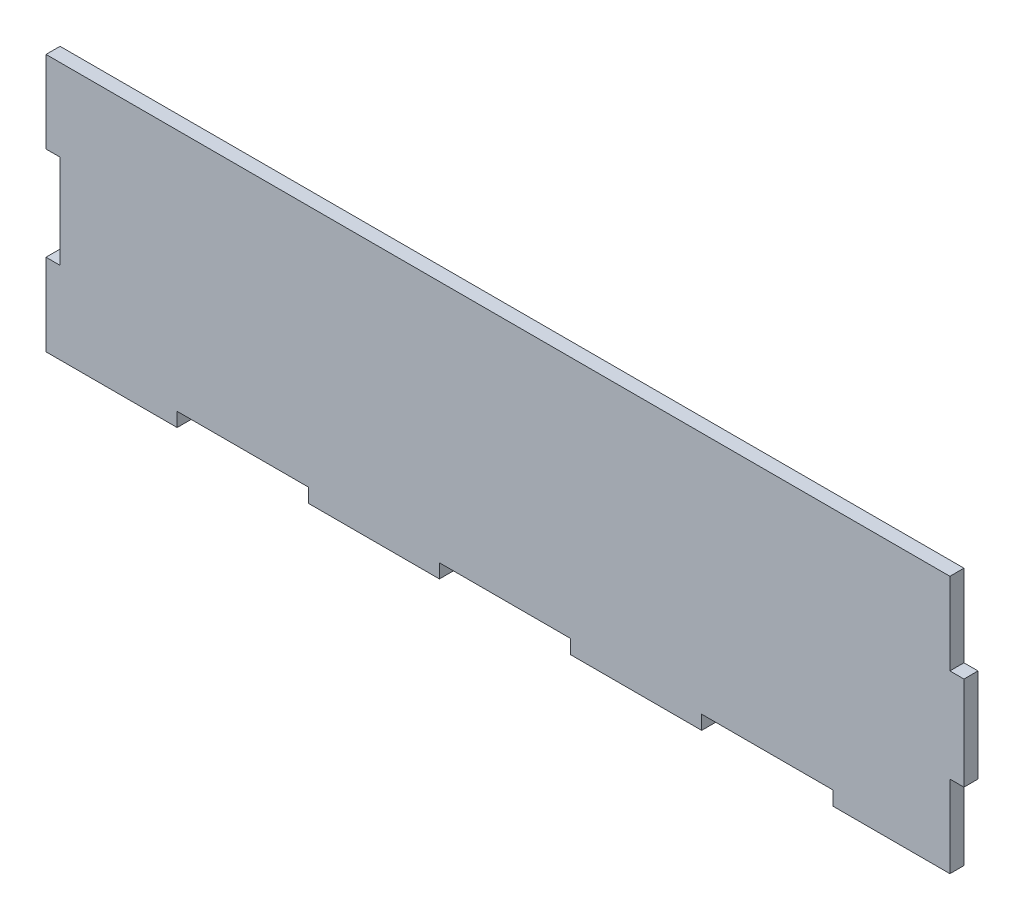
SolidWorks part; units mm, degrees
ref_plane "Front Plane" through (0, 0, 0) normal (0, 0, 1) x (1, 0, 0)
ref_plane "Top Plane" through (0, 0, 0) normal (0, 1, 0) x (1, 0, 0)
ref_plane "Right Plane" through (0, 0, 0) normal (1, 0, 0) x (0, 0, -1)
sketch "Sketch1" plane through (0, 0, 0) normal (0, 0, 1) x (1, 0, 0)
  line L0 (-98, -10) -> (-95, -10)
  line L1 (-98, -27.5) -> (98, -27.5)
  line L2 (-98, -27.5) -> (-98, 27.5)
  line L3 (-98, 27.5) -> (98, 27.5)
  line L4 (98, -27.5) -> (98, 27.5)
  line L5 (-98, -27.5) -> (98, 27.5) construction
  line L6 (-98, 27.5) -> (98, -27.5) construction
  line L7 (-95, -10) -> (-95, 10)
  line L8 (-95, 10) -> (-98, 10)
  line L9 (98, -10) -> (95, -10)
  line L10 (95, -10) -> (95, -27.5)
  line L11 (98, 10) -> (95, 10)
  line L12 (95, 10) -> (95, 27.5)
  line L14 (-70, -27.5) -> (-70, -24.5)
  line L15 (-70, -24.5) -> (-42, -24.5)
  line L16 (-42, -24.5) -> (-42, -27.5)
  line L18 (-14, -27.5) -> (-14, -24.5)
  line L19 (-14, -24.5) -> (14, -24.5)
  line L20 (14, -24.5) -> (14, -27.5)
  line L22 (42, -27.5) -> (42, -24.5)
  line L23 (42, -24.5) -> (70, -24.5)
  line L24 (70, -24.5) -> (70, -27.5)
  point P0 (0, 0)
  dimension "D1" = 196
  dimension "D2" = 55
  dimension "D3" = 20
  dimension "D4" = 17.5
  dimension "D5" = 3
  dimension "D6" = 3
  dimension "D7" = 3
  dimension "D8" = 28
  dimension "D9" = 28
  dimension "D10" = 28
  dimension "D11" = 28
  dimension "D12" = 28
  dimension "D13" = 28
  dimension "D14" = 3
  dimension "D15" = 20
extrude "Boss-Extrude1" add sketch "Sketch1" along normal blind 3 contours L23 L24 L1 L10 L9 L4 L11 L12 L3 L2 L8 L7 L0 L14 L15 L16 L18 L19 L20 L22
